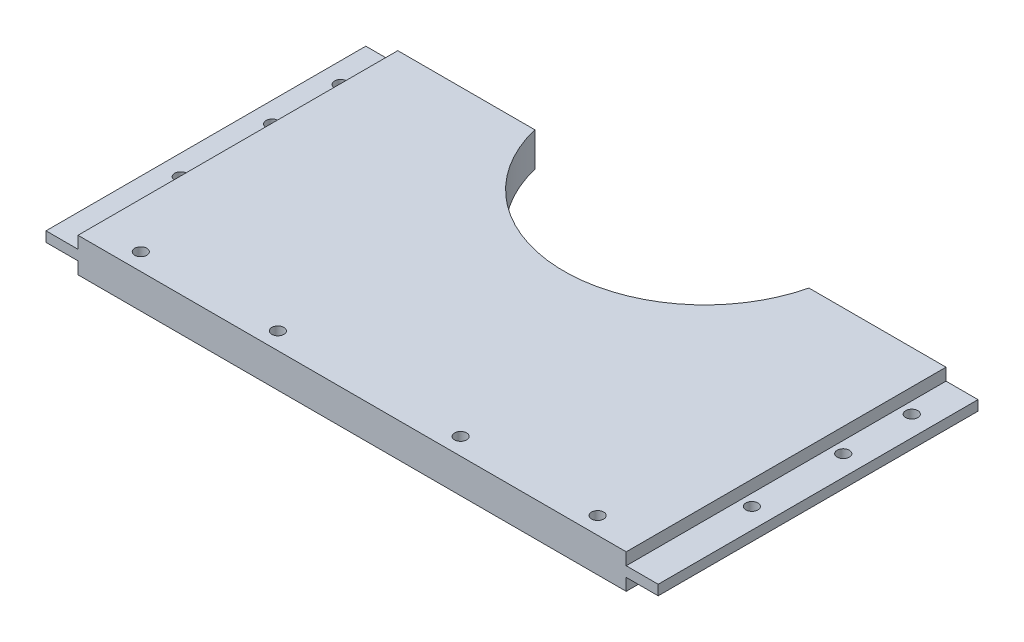
SolidWorks part; units mm, degrees
ref_plane "Front Plane" through (0, 0, 0) normal (0, 0, 1) x (1, 0, 0)
ref_plane "Top Plane" through (0, 0, 0) normal (0, 1, 0) x (1, 0, 0)
ref_plane "Right Plane" through (0, 0, 0) normal (1, 0, 0) x (0, 0, -1)
sketch "Sketch1" plane through (0, 0, 0) normal (0, 1, 0) x (1, 0, 0)
  line L0 (-152.4, 88.9) -> (-152.4, -88.9)
  line L1 (-152.4, -88.9) -> (152.4, -88.9)
  line L2 (152.4, -88.9) -> (152.4, 88.9)
  line L3 (0, -55) -> (0, 55) construction
  line L4 (-55, 0) -> (55, 0) construction
  line L5 (-152.4, 88.9) -> (-76.2, 88.9)
  line L6 (152.4, 88.9) -> (76.2, 88.9)
  circle A1 centre (0, 107.2651) radius 78.3819
  point P3 (0, 0)
  point P5 (0, -88.9)
  point P8 (152.4, 0)
  point P15 (-4.7574, 128.9596)
  point P16 (0, 0)
  point P17 (0, 107.2651)
  dimension "D1" = 304.8
  dimension "D2" = 177.8
  dimension "D3" = 76.2
extrude "Boss-Extrude1" add sketch "Sketch1" along normal mid plane 19.05 contours A1 L5 L0 L1 L2 L6
sketch "Sketch2" plane through (0, 0, 0) normal (0, 1, 0) x (1, 0, 0)
  line L0 (-152.4, -88.9) -> (152.4, -88.9) construction
  line L1 (-152.4, 88.9) -> (-170.18, 88.9)
  line L2 (-152.4, 88.9) -> (-152.4, -88.9)
  line L3 (-152.4, -88.9) -> (-170.18, -88.9)
  line L4 (-170.18, 88.9) -> (-170.18, -88.9)
  line L5 (152.4, 88.9) -> (170.18, 88.9)
  line L6 (152.4, 88.9) -> (152.4, -88.9)
  line L7 (152.4, -88.9) -> (170.18, -88.9)
  line L8 (170.18, 88.9) -> (170.18, -88.9)
  dimension "D1" = 17.78
  dimension "D2" = 17.78
extrude "Boss-Extrude2" add sketch "Sketch2" along normal mid plane 5.588
sketch "Sketch3" plane through (0, 2.794, 0) normal (0, 1, 0) x (1, 0, 0)
  line L0 (152.4, -88.9) -> (152.4, 88.9) construction
  line L1 (170.18, 88.9) -> (152.4, 88.9) construction
  point P0 (158.75, 63.5)
  point P1 (158.75, 25.4)
  point P2 (158.75, -25.4)
  point P3 (0, 0)
  point P4 (0, 0)
  dimension "D1" = 6.35
  dimension "D2" = 25.4
  dimension "D3" = 38.1
  dimension "D4" = 50.8
hole_wizard "1/4 Clearance Hole1" positions "Sketch4" profile "Sketch5" hole size "1/4" standard "ANSI Inch" end condition up to next
sketch "Sketch4" plane through (0, 2.794, 0) normal (0, 1, 0) x (1, 0, 0)
  point P0 (158.75, 63.5)
  point P3 (158.75, 25.4)
  point P6 (158.75, -25.4)
sketch "Sketch5" plane through (158.75, 2.794, -63.5) normal (1, 0, 0) x (0, 0, 1)
  line L0 (0, 0) -> (0, 5.588)
  line L1 (0, 5.588) -> (3.3782, 5.588)
  line L2 (3.3782, 5.588) -> (3.3782, 0)
  line L5 (3.3782, 0) -> (0, 0)
  line L11 (0, -6.35) -> (0, 107.95) construction
  dimension "Thru Hole Dia." = 6.7564
  dimension "Thru Hole Depth" = 5.588
mirror "Mirror1" about plane through (0, 0, 0) normal (1, 0, 0) of "1/4 Clearance Hole1"
sketch "Sketch6" plane through (0, 9.525, 0) normal (0, 1, 0) x (1, 0, 0)
  line L0 (-152.4, -88.9) -> (-152.4, 88.9) construction
  line L1 (-152.4, -88.9) -> (152.4, -88.9) construction
  point P0 (-127, -79.375)
  point P1 (-50.8, -79.375)
  point P2 (0, 0)
  point P4 (0, 0)
  point P6 (0, 0)
  dimension "D1" = 25.4
  dimension "D2" = 76.2
  dimension "D3" = 9.525
hole_wizard "1/4 Clearance Hole2" positions "Sketch7" profile "Sketch8" hole size "1/4" standard "ANSI Inch" end condition up to next
sketch "Sketch7" plane through (0, 9.525, 0) normal (0, 1, 0) x (1, 0, 0)
  point P0 (-127, -79.375)
  point P3 (-50.8, -79.375)
sketch "Sketch8" plane through (-127, 9.525, 79.375) normal (1, 0, 0) x (0, 0, 1)
  line L0 (0, 0) -> (0, 19.05)
  line L1 (0, 19.05) -> (3.3782, 19.05)
  line L2 (3.3782, 19.05) -> (3.3782, 0)
  line L5 (3.3782, 0) -> (0, 0)
  line L11 (0, -6.35) -> (0, 107.95) construction
  dimension "Thru Hole Dia." = 6.7564
  dimension "Thru Hole Depth" = 19.05
mirror "Mirror2" about plane through (0, 0, 0) normal (1, 0, 0) of "1/4 Clearance Hole2"
